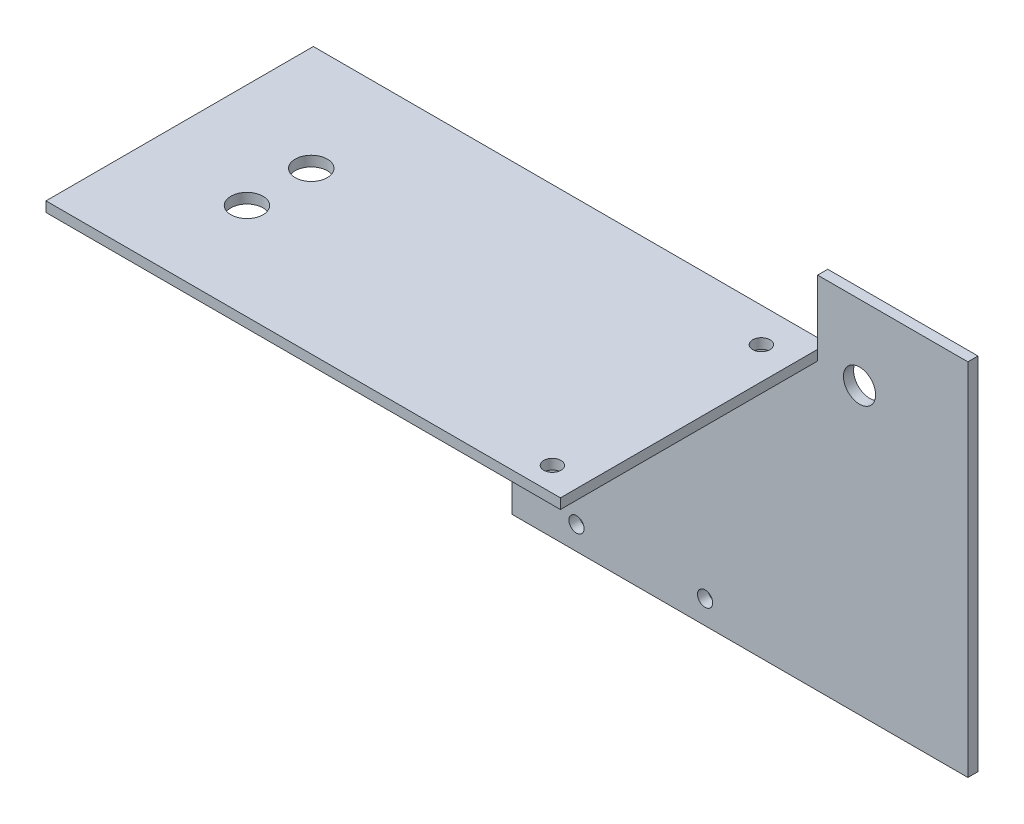
SolidWorks part; units mm, degrees
material "Galvanized Steel"
ref_plane "Front Plane" through (0, 0, 0) normal (0, 0, 1) x (1, 0, 0)
ref_plane "Top Plane" through (0, 0, 0) normal (0, 1, 0) x (1, 0, 0)
ref_plane "Right Plane" through (0, 0, 0) normal (1, 0, 0) x (0, 0, -1)
sketch "Sketch1" plane through (0, 0, 0) normal (0, 0, 1) x (1, 0, 0)
  line L0 (38.1, 51.75) -> (12.7, 51.75) construction
  line L1 (0, 58.4) -> (60.325, 58.4)
  line L2 (0, 58.4) -> (0, 0)
  line L3 (0, 0) -> (90, 0)
  line L4 (90, 58.4) -> (90, 0)
  line L5 (90, 58.4) -> (90, 71.1)
  line L6 (12.7, 51.75) -> (12.7, 4.65) construction
  line L7 (90, 71.1) -> (60.325, 71.1)
  line L8 (12.7, 4.65) -> (38.1, 4.65) construction
  line L9 (38.1, 51.75) -> (38.1, 4.65) construction
  line L10 (60.325, 71.1) -> (60.325, 58.4)
  circle A0 centre (68.6, 56.332) radius 3.175
  circle A4 centre (12.7, 51.75) radius 1.5
  circle A5 centre (38.1, 51.75) radius 1.5
  circle A6 centre (12.7, 4.65) radius 1.5
  circle A7 centre (38.1, 4.65) radius 1.5
  dimension "D3" = 3
  dimension "D10" = 2.068
  dimension "D5" = 6.35
  dimension "D1" = 58.4
  dimension "D2" = 90
  dimension "D4" = 47.1
  dimension "D6" = 4.65
  dimension "D7" = 25.4
  dimension "D8" = 21.4
  dimension "D9" = 12.7
  dimension "D11" = 60.325
  dimension "D12" = 12.7
extrude "Boss-Extrude1" add sketch "Sketch1" against normal blind 2
sketch "Sketch2" plane through (0, 0, -2) normal (0, 0, -1) x (-1, 0, 0)
  line L0 (0, 56.4) -> (41.275, 56.4)
  line L1 (0, 58.4) -> (0, 0) construction
  line L2 (0, 56.4) -> (-60.325, 56.4)
  line L3 (-60.325, 56.4) -> (-60.325, 58.4)
  line L5 (-60.325, 58.4) -> (0, 58.4)
  line L6 (41.275, 56.4) -> (41.275, 58.4)
  line L7 (41.275, 58.4) -> (0, 58.4)
  dimension "D1" = 60.325
  dimension "D2" = 41.275
  dimension "D3" = 2
extrude "Boss-Extrude2" add sketch "Sketch2" against normal blind 52.8
sketch "Sketch3" plane through (0, 58.4, 0) normal (0, 1, 0) x (1, 0, 0)
  line L0 (53.975, -4.7625) -> (53.975, -46.0375) construction
  line L1 (-20.6375, -19.05) -> (-20.6375, -31.75) construction
  line L2 (60.325, -50.8) -> (60.325, 0) construction
  line L3 (-41.275, -50.8) -> (60.325, -50.8) construction
  line L4 (-41.275, -50.8) -> (60.325, -50.8) construction
  line L5 (-41.275, -50.8) -> (-41.275, 2) construction
  circle A0 centre (53.975, -4.7625) radius 1.7
  circle A1 centre (53.975, -46.0375) radius 1.7
  circle A2 centre (-20.6375, -31.75) radius 3.175
  circle A3 centre (-20.6375, -19.05) radius 3.175
  dimension "D1" = 3.4
  dimension "D2" = 41.275
  dimension "D5" = 6.35
  dimension "D6" = 6.35
  dimension "D3" = 4.7625
  dimension "D4" = 6.35
  dimension "D7" = 12.7
  dimension "D8" = 19.05
  dimension "D9" = 20.6375
extrude "Cut-Extrude1" cut sketch "Sketch3" against normal through all
